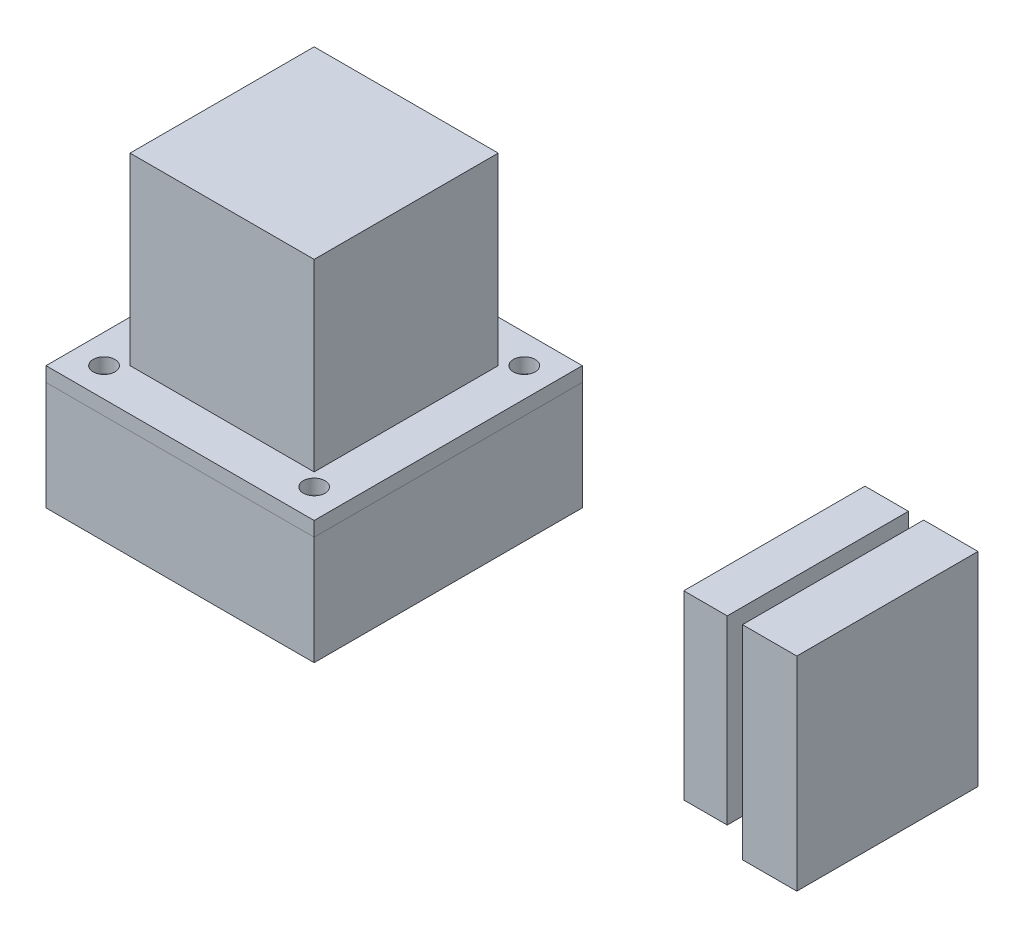
SolidWorks part; units mm, degrees
ref_plane "Front Plane" through (0, 0, 0) normal (0, 0, 1) x (1, 0, 0)
ref_plane "Top Plane" through (0, 0, 0) normal (0, 1, 0) x (1, 0, 0)
ref_plane "Right Plane" through (0, 0, 0) normal (1, 0, 0) x (0, 0, -1)
sketch "Sketch1" plane through (0, 0, 0) normal (1, 0, 0) x (0, 0, -1)
  line L1 (-12.5, 12.5) -> (12.5, 12.5)
  line L2 (-12.5, 12.5) -> (-12.5, -12.5)
  line L3 (-12.5, -12.5) -> (12.5, -12.5)
  line L4 (12.5, 12.5) -> (12.5, -12.5)
  line L5 (-12.5, 12.5) -> (12.5, -12.5) construction
  line L6 (-12.5, -12.5) -> (12.5, 12.5) construction
  point P0 (0, 0)
  dimension "D1" = 25
  dimension "D2" = 25
extrude "Boss-Extrude1" add sketch "Sketch1" along normal blind 6
ref_plane "Plane1" through (15.6, 0, 0) normal (-1, 0, 0) x (0, 0, 1)
sketch "Sketch3" plane through (15.6, 0, 0) normal (-1, 0, 0) x (0, 0, 1)
  line L0 (-12.5, 12.5) -> (12.5, 12.5)
  line L1 (12.5, 12.5) -> (12.5, -15.6)
  line L2 (12.5, -15.6) -> (-12.5, -15.6)
  line L3 (-12.5, -15.6) -> (-12.5, 12.5)
  dimension "D1" = 28.1
extrude "Boss-Extrude2" add sketch "Sketch3" along normal blind 7.5 separate body
sketch "Sketch5" plane through (0, -15.6, 0) normal (0, -1, 0) x (1, 0, 0)
  line L0 (8.1, 12.5) -> (20.6, 12.5)
  line L1 (15.6, 13.75) -> (15.6, -13.75) construction
  line L2 (20.6, 12.5) -> (20.6, -12.5)
  line L3 (8.1, -12.5) -> (20.6, -12.5)
  line L4 (20.6, 0) -> (44.6, 0)
  line L5 (44.6, 0) -> (44.6, 2.5)
  line L6 (44.6, 2.5) -> (20.6, 2.5)
  line L7 (44.6, 0) -> (44.6, -2.5)
  line L8 (44.6, -2.5) -> (20.6, -2.5)
  line L9 (20.6, -12.5) -> (32.6, -12.5)
  line L10 (32.6, -12.5) -> (32.6, -2.5)
  line L11 (8.1, -12.5) -> (8.1, -30)
  line L12 (8.1, -30) -> (58.1, -30)
  line L13 (58.1, -30) -> (58.1, 30)
  line L14 (58.1, 0) -> (44.6, 0)
  line L15 (8.1, 12.5) -> (8.1, 30)
  line L16 (8.1, 30) -> (58.1, 30)
  dimension "D1" = 5
  dimension "D2" = 2.5
  dimension "D3" = 24
  dimension "D4" = 2.5
  dimension "D5" = 12
  dimension "D6" = 50
  dimension "D7" = 30
sketch "Sketch6" plane through (0, -15.6, 0) normal (0, -1, 0) x (1, 0, 0)
  line L0 (8.1, 30) -> (58.1, 30) construction
  line L1 (8.1, 12.5) -> (8.1, 30) construction
  line L2 (58.1, -30) -> (58.1, 30) construction
  line L3 (8.1, -30) -> (58.1, -30) construction
  line L4 (8.1, -12.5) -> (8.1, -30) construction
  line L5 (20.6, -12.5) -> (32.6, -12.5) construction
  line L6 (8.1, -12.5) -> (20.6, -12.5) construction
  line L7 (32.6, -12.5) -> (32.6, -2.5) construction
  line L8 (44.6, -2.5) -> (20.6, -2.5) construction
  line L9 (44.6, 0) -> (44.6, -2.5) construction
  line L10 (44.6, 0) -> (44.6, 2.5) construction
  line L11 (44.6, 2.5) -> (20.6, 2.5) construction
  line L12 (20.6, 12.5) -> (20.6, -12.5) construction
  line L13 (8.1, 12.5) -> (20.6, 12.5) construction
  line L14 (8.1, 30) -> (58.1, 30)
  line L15 (8.1, 12.5) -> (8.1, 30)
  line L16 (58.1, -30) -> (58.1, 30)
  line L17 (8.1, -30) -> (58.1, -30)
  line L18 (8.1, -12.5) -> (8.1, -30)
  line L19 (20.6, -12.5) -> (32.6, -12.5)
  line L20 (8.1, -12.5) -> (20.6, -12.5)
  line L21 (32.6, -12.5) -> (32.6, -2.5)
  line L22 (44.6, -2.5) -> (32.6, -2.5)
  line L23 (44.6, 0) -> (44.6, -2.5)
  line L24 (44.6, 0) -> (44.6, 2.5)
  line L25 (44.6, 2.5) -> (20.6, 2.5)
  line L26 (20.6, 12.5) -> (20.6, 2.5)
  line L27 (8.1, 12.5) -> (20.6, 12.5)
sketch "Sketch7" plane through (0, -15.6, 0) normal (0, -1, 0) x (1, 0, 0)
  line L0 (8.1, 0) -> (84.1, 0)
  line L1 (8.1, -12.5) -> (8.1, 12.5) construction
  line L2 (84.1, -38) -> (84.1, 38)
  line L3 (84.1, 38) -> (8.1, 38)
  line L4 (8.1, 38) -> (8.1, -38)
  line L5 (8.1, -38) -> (84.1, -38)
  line L6 (46.1, 0) -> (46.1, -11.58)
  line L7 (-21, 12.5) -> (-21, -12.5)
  line L8 (15.6, 13.75) -> (15.6, -13.75) construction
  line L9 (8.1, 0) -> (-21, 0)
  circle A0 centre (46.1, 0) radius 3
  circle A1 centre (71.1902, 0) radius 3
  circle A2 centre (21.0098, 0) radius 3
  circle A3 centre (21.0098, 25) radius 3
  circle A4 centre (46.1, 25) radius 3
  circle A5 centre (71.1902, 25) radius 3
  circle A6 centre (71.1902, -25) radius 3
  circle A7 centre (46.1, -25) radius 3
  circle A8 centre (21.0098, -25) radius 3
  dimension "D3" = 6
  dimension "D4" = 6
  dimension "D1" = 76
  dimension "D2" = 38
  dimension "D6" = 36.6
  dimension "D5" = 2
sketch "Sketch8" plane through (0, -15.6, 0) normal (0, -1, 0) x (1, 0, 0)
  line L0 (-21, 0) -> (-23, 0)
  line L1 (-21, 12.5) -> (-21, -12.5) construction
  line L2 (-76.2, 12.7) -> (-50.8, 12.7)
  line L3 (-76.2, 12.7) -> (-76.2, -12.7)
  line L4 (-76.2, -12.7) -> (-50.8, -12.7)
  line L5 (-50.8, 12.7) -> (-50.8, -12.7)
  line L6 (-76.2, 12.7) -> (-50.8, -12.7) construction
  line L7 (-76.2, -12.7) -> (-50.8, 12.7) construction
  line L8 (-82, 18.5) -> (-45, 18.5)
  line L9 (-82, 18.5) -> (-82, -18.5)
  line L10 (-82, -18.5) -> (-45, -18.5)
  line L11 (-45, 18.5) -> (-45, -18.5)
  line L12 (-82, 18.5) -> (-45, -18.5) construction
  line L13 (-82, -18.5) -> (-45, 18.5) construction
  line L14 (-63.5, 0) -> (-45, 0)
  line L15 (-23, 0) -> (-45, 0)
  line L16 (-63.5, 0) -> (-63.5, 42.5)
  line L17 (-45.5, 42.5) -> (-81.5, 42.5)
  circle A0 centre (-49.0043, 14.4957) radius 1.5
  circle A1 centre (-49.0043, -14.4957) radius 1.5
  circle A2 centre (-77.9957, -14.4957) radius 1.5
  circle A3 centre (-77.9957, 14.4957) radius 1.5
  point P29 (-63.5, 0)
  dimension "D6" = 3
  dimension "D1" = 2
  dimension "D2" = 25.4
  dimension "D3" = 25.4
  dimension "D4" = 37
  dimension "D5" = 37
  dimension "D7" = 18.5
  dimension "D9" = 22
  dimension "D10" = 42.5
  dimension "D11" = 42.5
  dimension "D12" = 18
  dimension "D13" = 36
  dimension "D8" = 4
ref_plane "Plane2" through (0, 0, 42.5) normal (0, 0, 1) x (1, 0, 0)
sketch "Sketch9" plane through (0, 0, 42.5) normal (0, 0, 1) x (1, 0, 0)
  line L0 (-63.5, -15.6) -> (-63.5, -10.6)
  line L1 (-45.5, -15.6) -> (-81.5, -15.6) construction
  dimension "D1" = 5
sketch "Sketch11" plane through (0, -15.6, 0) normal (0, -1, 0) x (1, 0, 0)
  line L0 (-76.2, -12.7) -> (-50.8, 12.7) construction
  line L1 (-82, -18.5) -> (-45, -18.5)
  line L2 (-82, -18.5) -> (-82, 18.5)
  line L3 (-82, 18.5) -> (-45, 18.5)
  line L4 (-45, -18.5) -> (-45, 18.5)
  line L5 (-82, -18.5) -> (-45, 18.5) construction
  line L6 (-82, 18.5) -> (-45, -18.5) construction
  circle A0 centre (-49.0043, 14.4957) radius 1.5 construction
  circle A1 centre (-49.0043, -14.4957) radius 1.5 construction
  circle A2 centre (-77.9957, -14.4957) radius 1.5 construction
  circle A3 centre (-77.9957, 14.4957) radius 1.5 construction
  circle A4 centre (-49.0043, 14.4957) radius 1.5
  circle A5 centre (-49.0043, -14.4957) radius 1.5
  circle A6 centre (-77.9957, -14.4957) radius 1.5
  circle A7 centre (-77.9957, 14.4957) radius 1.5
  point P0 (-63.5, 0)
extrude "Boss-Extrude4" add sketch "Sketch11" against normal blind 15 separate body
sketch "Sketch12" plane through (0, -0.6, 0) normal (0, 1, 0) x (1, 0, 0)
  line L4 (-45, 18.5) -> (-82, 18.5)
  line L5 (-45, -18.5) -> (-45, 18.5)
  line L6 (-82, -18.5) -> (-45, -18.5)
  line L7 (-82, 18.5) -> (-82, -18.5)
  line L8 (-45, 18.5) -> (-82, 18.5)
  line L9 (-45, -18.5) -> (-45, 18.5)
  line L10 (-82, -18.5) -> (-45, -18.5)
  line L11 (-82, 18.5) -> (-82, -18.5)
  circle A1 centre (-77.9957, -14.4957) radius 1.5
  circle A2 centre (-77.9957, -14.4957) radius 1.5
  circle A3 centre (-77.9957, 14.4957) radius 1.5
  circle A4 centre (-77.9957, 14.4957) radius 1.5
  circle A5 centre (-49.0043, 14.4957) radius 1.5
  circle A6 centre (-49.0043, 14.4957) radius 1.5
  circle A7 centre (-49.0043, -14.4957) radius 1.5
  circle A8 centre (-49.0043, -14.4957) radius 1.5
  dimension "D1" = 0
  dimension "D2" = 0
  dimension "D3" = 0
  dimension "D4" = 0
  dimension "D5" = 0
extrude "Boss-Extrude5" add sketch "Sketch12" along normal blind 2 separate body
sketch "Sketch13" plane through (0, 1.4, 0) normal (0, 1, 0) x (1, 0, 0)
  line L1 (-76.2, -12.7) -> (-50.8, -12.7)
  line L2 (-76.2, -12.7) -> (-76.2, 12.7)
  line L3 (-76.2, 12.7) -> (-50.8, 12.7)
  line L4 (-50.8, -12.7) -> (-50.8, 12.7)
  line L5 (-76.2, -12.7) -> (-50.8, 12.7) construction
  line L6 (-76.2, 12.7) -> (-50.8, -12.7) construction
  point P0 (-63.5, 0)
extrude "Boss-Extrude6" add sketch "Sketch13" along normal blind 25.4 separate body
